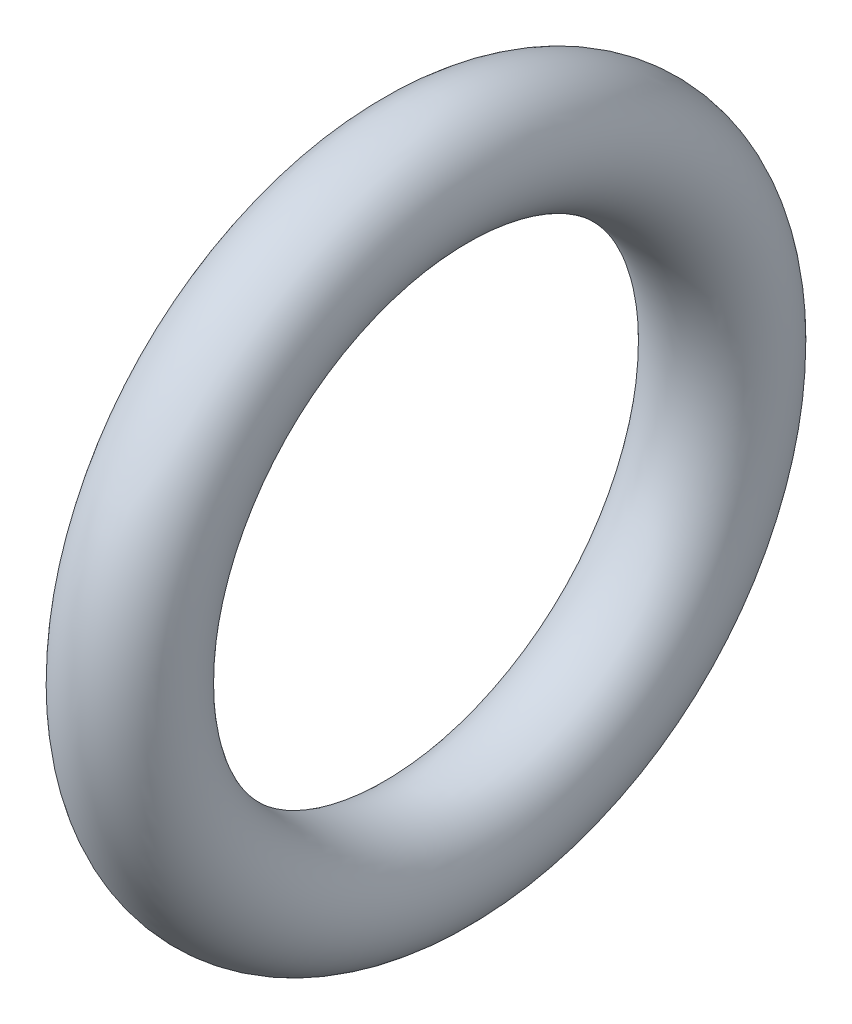
SolidWorks part; units mm, degrees
ref_plane "Face" through (0, 0, 0) normal (0, 0, 1) x (1, 0, 0)
ref_plane "Dessus" through (0, 0, 0) normal (0, 1, 0) x (1, 0, 0)
ref_plane "Droite" through (0, 0, 0) normal (1, 0, 0) x (0, 0, -1)
sketch "Esquisse1" plane through (0, 0, 0) normal (0, 0, 1) x (1, 0, 0)
  line L0 (-17.272, 0) -> (18.3083, 0) construction
  circle A0 centre (0, 6.25) radius 1.25
  dimension "D1" = 2.5
  dimension "D2" = 6.25
revolve "Révolution1" add sketch "Esquisse1" angle 360 about L0
